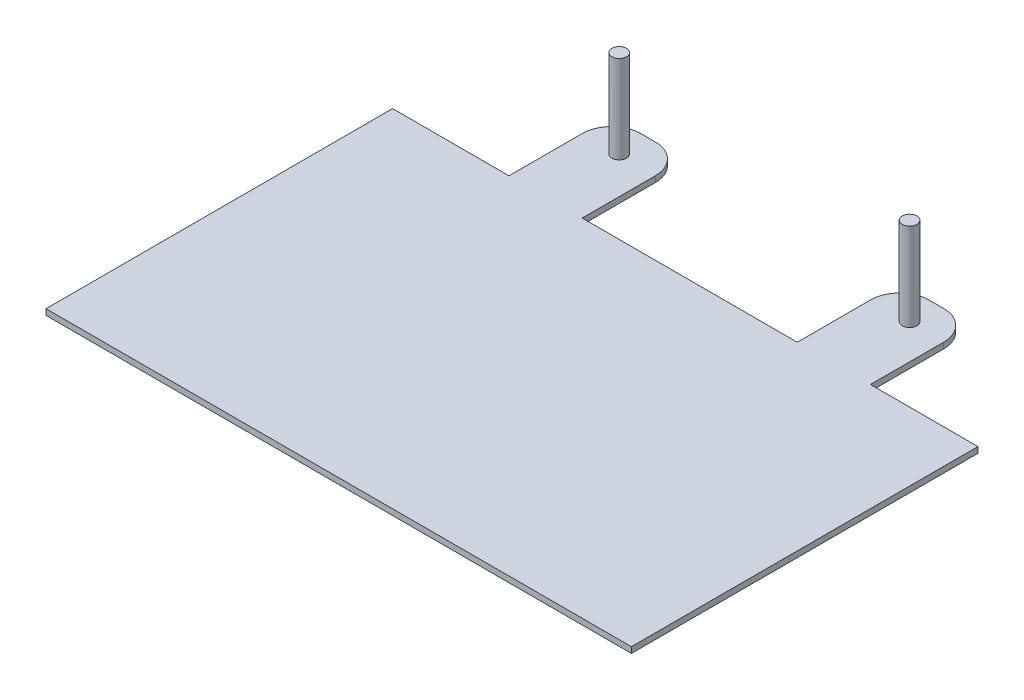
SolidWorks part; units mm, degrees
ref_plane "前视基准面" through (0, 0, 0) normal (0, 0, 1) x (1, 0, 0)
ref_plane "上视基准面" through (0, 0, 0) normal (0, 1, 0) x (1, 0, 0)
ref_plane "右视基准面" through (0, 0, 0) normal (1, 0, 0) x (0, 0, -1)
other "Configuration Table"
sketch "草图1" plane through (0, 0, 0) normal (0, 1, 0) x (1, 0, 0)
  line L0 (64.7727, 118.4091) -> (138.2576, 118.4091)
  line L1 (0, 0) -> (200, 0)
  line L2 (0, 0) -> (0, 118.4091)
  line L3 (0, 118.4091) -> (39.7727, 118.4091)
  line L4 (200, 0) -> (200, 118.4091)
  line L6 (39.7727, 118.4091) -> (39.7727, 143.4091)
  line L7 (49.7727, 153.4091) -> (54.7727, 153.4091)
  line L8 (64.7727, 118.4091) -> (64.7727, 143.4091)
  line L10 (138.2576, 118.4091) -> (138.2576, 143.4091)
  line L11 (148.2576, 153.4091) -> (153.2576, 153.4091)
  line L12 (163.2576, 118.4091) -> (163.2576, 143.4091)
  line L13 (163.2576, 118.4091) -> (200, 118.4091)
  arc A0 (153.2576, 153.4091) -> (163.2576, 143.4091) centre (153.2576, 143.4091) cw
  arc A1 (138.2576, 143.4091) -> (148.2576, 153.4091) centre (148.2576, 143.4091) cw
  arc A2 (54.7727, 153.4091) -> (64.7727, 143.4091) centre (54.7727, 143.4091) cw
  arc A3 (39.7727, 143.4091) -> (49.7727, 153.4091) centre (49.7727, 143.4091) cw
  point P15 (163.2576, 153.4091)
  point P18 (138.2576, 153.4091)
  point P21 (64.7727, 153.4091)
  point P24 (39.7727, 153.4091)
  dimension "D5" = 10
  dimension "D1" = 200
  dimension "D2" = 25
  dimension "D3" = 25
  dimension "D4" = 0
extrude "凸台-拉伸1" add sketch "草图1" along normal blind 2
sketch "草图2" plane through (0, 2, 0) normal (0, 1, 0) x (1, 0, 0)
  circle A0 centre (52.1192, 143.6956) radius 2.5
  circle A1 centre (151.3282, 143.6956) radius 2.5
  dimension "D1" = 5
  dimension "D2" = 5
extrude "凸台-拉伸2" add sketch "草图2" along normal blind 30
